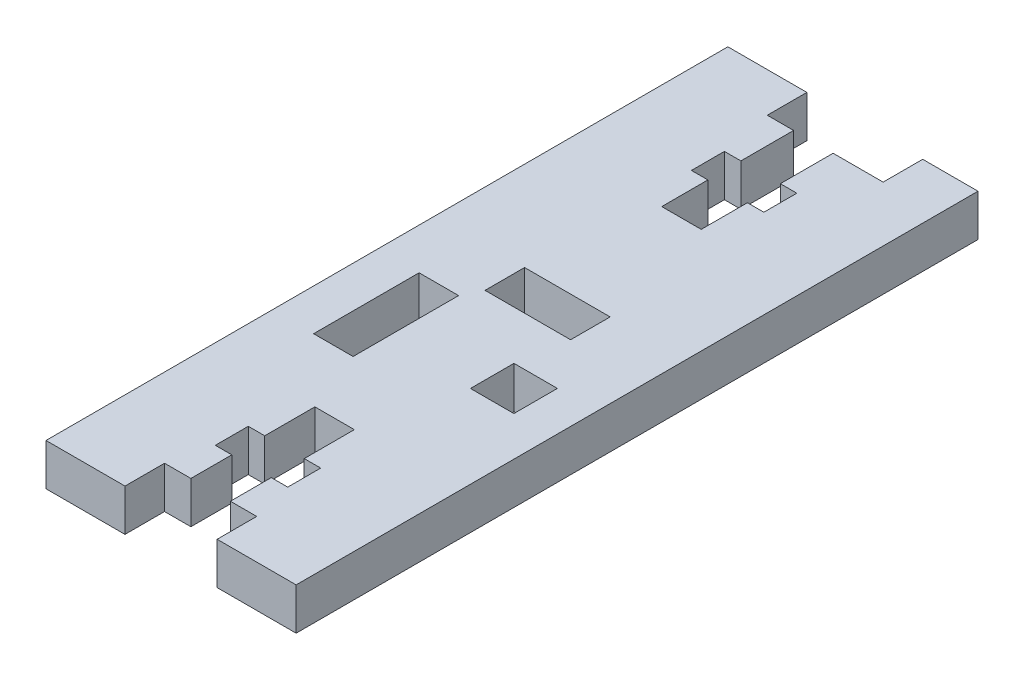
SolidWorks part; units mm, degrees
material "Acrylic (Medium-high impact)"
ref_plane "Front Plane" through (0, 0, 0) normal (0, 0, 1) x (1, 0, 0)
ref_plane "Top Plane" through (0, 0, 0) normal (0, 1, 0) x (1, 0, 0)
ref_plane "Right Plane" through (0, 0, 0) normal (1, 0, 0) x (0, 0, -1)
sketch "Sketch1" plane through (0, 0, 0) normal (0, 1, 0) x (1, 0, 0)
  line L0 (9.8429, -27.4833) -> (3.8536, -27.4833)
  line L1 (-9.1233, -27.4833) -> (-9.1233, 24.2185)
  line L2 (-9.1233, 24.2185) -> (-3.1341, 24.2185)
  line L3 (9.8429, 24.2185) -> (9.8429, -27.4833)
  line L4 (-3.1341, 24.2185) -> (-3.1341, 21.2185)
  line L5 (-3.1341, 21.2185) -> (-1.1376, 21.2185)
  line L6 (-1.1376, 21.2185) -> (-1.1376, 17.2183)
  line L7 (-1.1376, 17.2183) -> (-2.3854, 17.2183)
  line L8 (-2.3854, 17.2183) -> (-2.3854, 14.7184)
  line L9 (-2.3854, 14.7184) -> (-1.1376, 14.7184)
  line L10 (-1.1376, 14.7184) -> (-1.1376, 11.2182)
  line L11 (-1.1376, 11.2182) -> (1.8573, 11.2182)
  line L12 (1.8573, 11.2182) -> (1.8573, 14.7184)
  line L13 (1.8573, 14.7184) -> (3.1051, 14.7184)
  line L14 (3.1051, 14.7184) -> (3.1051, 17.2183)
  line L15 (3.1051, 17.2183) -> (1.8573, 17.2183)
  line L16 (1.8573, 17.2183) -> (1.8573, 21.2185)
  line L17 (1.8573, 21.2185) -> (5.6504, 21.2185)
  line L18 (5.6504, 21.2185) -> (5.6504, 24.2187)
  line L19 (-3.1341, -27.4833) -> (-3.1341, -24.4832)
  line L20 (-3.1341, -24.4832) -> (-1.1376, -24.4832)
  line L21 (-1.1376, -24.4832) -> (-3.1341, -24.4832)
  line L22 (3.8536, -24.4832) -> (1.8573, -24.4832)
  line L23 (1.8573, -24.4832) -> (3.8536, -24.4832)
  line L24 (3.8536, -24.4832) -> (3.8536, -27.4833)
  line L25 (4.1531, -0.9822) -> (4.1531, 2.0177)
  line L26 (4.1531, 2.0177) -> (-2.3354, 2.0177)
  line L27 (-2.3354, 2.0177) -> (-2.3354, -0.9822)
  line L28 (-2.3354, -0.9822) -> (4.1531, -0.9822)
  line L29 (1.8573, -24.4832) -> (1.8573, -21.3831)
  line L30 (1.8573, -21.3831) -> (3.1051, -21.3831)
  line L31 (3.1051, -21.3831) -> (3.1051, -18.883)
  line L32 (3.1051, -18.883) -> (1.8573, -18.883)
  line L33 (1.8573, -18.883) -> (1.8573, -15.0828)
  line L34 (1.8573, -15.0828) -> (-1.1376, -15.0828)
  line L35 (-1.1376, -15.0828) -> (-1.1376, -18.883)
  line L36 (-1.1376, -18.883) -> (-2.3854, -18.883)
  line L37 (-2.3854, -18.883) -> (-2.3854, -21.3831)
  line L38 (-2.3854, -21.3831) -> (-1.1376, -21.3831)
  line L39 (-1.1376, -21.3831) -> (-1.1376, -24.4832)
  line L40 (3.5542, -7.9784) -> (6.8484, -7.9784)
  line L41 (6.8484, -7.9784) -> (6.8484, -4.6781)
  line L42 (6.8484, -4.6781) -> (3.5542, -4.6781)
  line L43 (3.5542, -4.6781) -> (3.5542, -7.9784)
  line L44 (-5.9878, -10.3284) -> (-2.9932, -10.3284)
  line L45 (-2.9932, -10.3284) -> (-2.9932, -2.3281)
  line L46 (-2.9932, -2.3281) -> (-5.9878, -2.3281)
  line L47 (-5.9878, -2.3281) -> (-5.9878, -10.3284)
  line L48 (5.6504, 24.2185) -> (9.8429, 24.2185)
  line L49 (-3.1341, -27.4833) -> (-9.1233, -27.4833)
extrude "Boss-Extrude1" add sketch "Sketch1" along normal blind 3.175 contours L49 L19 L20 L39 L38 L37 L36 L35 L34 L33 L32 L31 L30 L29 L22 L24 L0 L3 L48 L18 L17 L16 L15 L14 L13 L12 L11 L10 L9 L8 L7 L6 L5 L4 L2 L1 L47 L46 L45 L44 L43 L42 L41 L40 L28 L27 L26 L25
